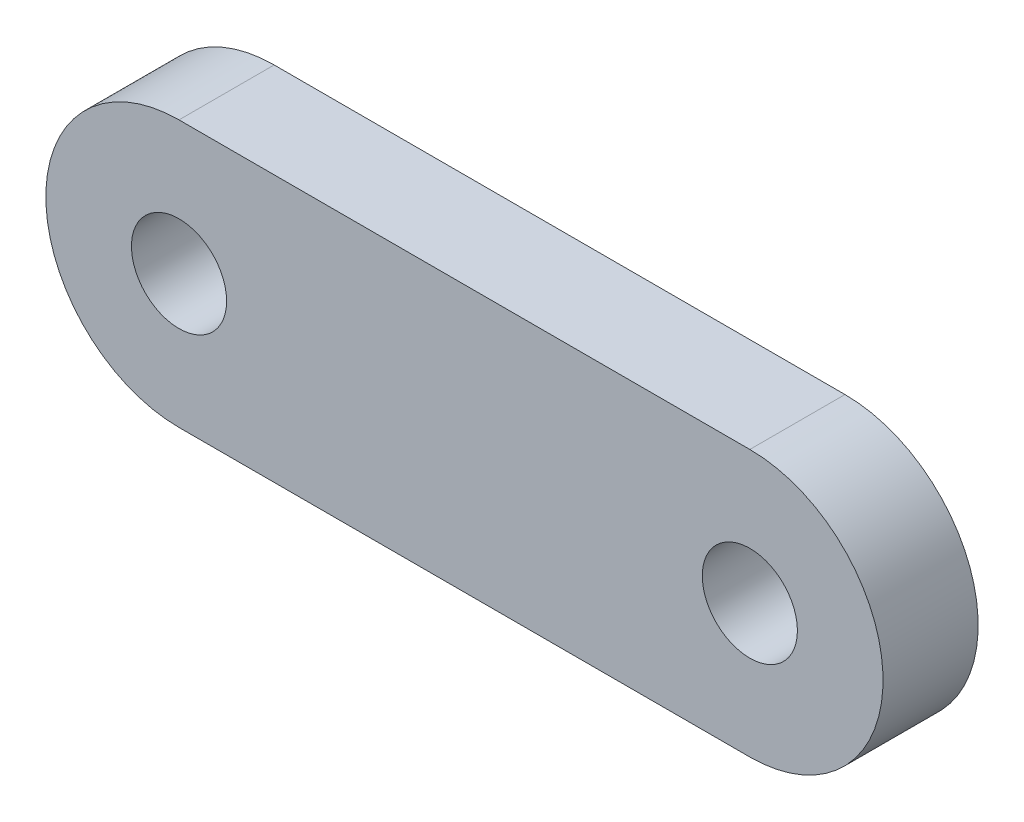
SolidWorks part; units mm, degrees
ref_plane "Front Plane" through (0, 0, 0) normal (0, 0, 1) x (1, 0, 0)
ref_plane "Top Plane" through (0, 0, 0) normal (0, 1, 0) x (1, 0, 0)
ref_plane "Right Plane" through (0, 0, 0) normal (1, 0, 0) x (0, 0, -1)
sketch "Sketch1" plane through (0, 0, 0) normal (0, 0, 1) x (1, 0, 0)
  line L1 (-19.05, -8.89) -> (19.05, -8.89)
  line L3 (-19.05, 8.89) -> (19.05, 8.89)
  line L5 (-19.05, -8.89) -> (19.05, 8.89) construction
  line L6 (-19.05, 8.89) -> (19.05, -8.89) construction
  arc A0 (-19.05, 8.89) -> (-19.05, -8.89) centre (-19.05, 0) ccw
  arc A1 (19.05, 8.89) -> (19.05, -8.89) centre (19.05, 0) cw
  circle A2 centre (-19.05, 0) radius 3.175
  circle A3 centre (19.05, 0) radius 3.175
  point P0 (0, 0)
  dimension "D3" = 6.35
  dimension "D1" = 38.1
  dimension "D2" = 17.78
extrude "Boss-Extrude1" add sketch "Sketch1" along normal blind 6.35
